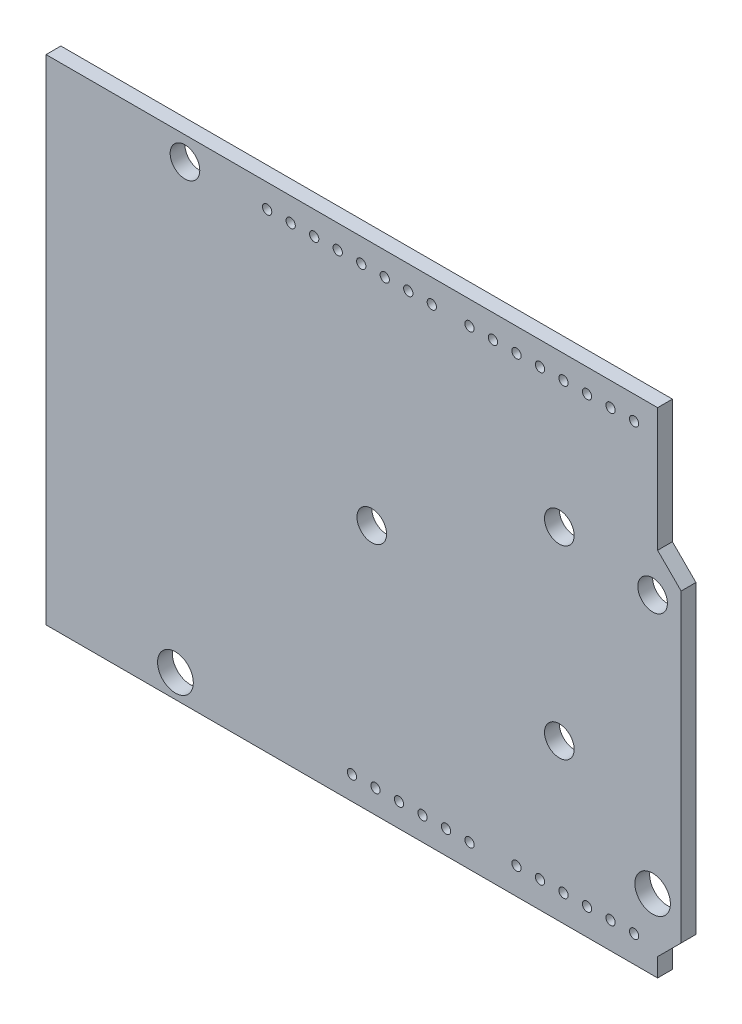
SolidWorks part; units mm, degrees
ref_plane "Front" through (0, 0, 0) normal (0, 0, 1) x (1, 0, 0)
ref_plane "Top" through (0, 0, 0) normal (0, 1, 0) x (1, 0, 0)
ref_plane "Right" through (0, 0, 0) normal (1, 0, 0) x (0, 0, -1)
sketch "草图1" plane through (0, 0, 0) normal (0, 0, 1) x (1, 0, 0)
  line L0 (0, 0) -> (66.04, 0)
  line L1 (66.04, 0) -> (66.04, -13.34)
  line L2 (66.04, -13.34) -> (68.58, -15.88)
  line L3 (68.58, -15.88) -> (68.58, -48.8)
  line L4 (68.58, -48.8) -> (66.04, -51.34)
  line L5 (66.04, -51.34) -> (66.04, -53.34)
  line L6 (66.04, -53.34) -> (0, -53.34)
  line L7 (0, -53.34) -> (0, 0)
  line L8 (45.7314, -50.8) -> (12.3544, -50.8) construction
  line L9 (0, -2.54) -> (66.04, -2.54) construction
  circle A0 centre (45.7314, -50.8) radius 0.5
  circle A1 centre (63.5, -50.46) radius 0.5
  circle A2 centre (43.1914, -50.8) radius 0.5
  circle A3 centre (40.6514, -50.8) radius 0.5
  circle A4 centre (38.1114, -50.8) radius 0.5
  circle A5 centre (35.5714, -50.8) radius 0.5
  circle A6 centre (33.0314, -50.8) radius 0.5
  circle A7 centre (60.96, -50.46) radius 0.5
  circle A8 centre (58.42, -50.46) radius 0.5
  circle A9 centre (55.88, -50.46) radius 0.5
  circle A10 centre (53.34, -50.46) radius 0.5
  circle A11 centre (50.8, -50.46) radius 0.5
  circle A12 centre (15, -2.54) radius 1.6
  circle A13 centre (41.656, -2.54) radius 0.5
  circle A14 centre (63.5, -2.54) radius 0.5
  circle A15 centre (39.116, -2.54) radius 0.5
  circle A16 centre (36.576, -2.54) radius 0.5
  circle A17 centre (34.036, -2.54) radius 0.5
  circle A18 centre (31.496, -2.54) radius 0.5
  circle A19 centre (28.956, -2.54) radius 0.5
  circle A20 centre (26.416, -2.54) radius 0.5
  circle A21 centre (23.876, -2.54) radius 0.5
  circle A22 centre (60.96, -2.54) radius 0.5
  circle A23 centre (58.42, -2.54) radius 0.5
  circle A24 centre (55.88, -2.54) radius 0.5
  circle A25 centre (53.34, -2.54) radius 0.5
  circle A26 centre (50.8, -2.54) radius 0.5
  circle A27 centre (48.26, -2.54) radius 0.5
  circle A28 centre (45.72, -2.54) radius 0.5
  circle A29 centre (13.97, -50.8) radius 1.9317
  circle A30 centre (65.5, -17.78) radius 1.5981
  circle A31 centre (65.5, -45.72) radius 1.9177
  point P77 (0, 0)
  dimension "D9" = 50.8
  dimension "D11" = 1
  dimension "D13" = 3.2
  dimension "D17" = 45.72
  dimension "D3" = 40
  dimension "D4" = 2
  dimension "D5" = 68.58
  dimension "D6" = 135
  dimension "D7" = 5.08
  dimension "D8" = 2.54
  dimension "D14" = 13.97
  dimension "D15" = 15
  dimension "D16" = 2.54
  dimension "D18" = 4.064
  dimension "D20" = 2.54
  dimension "D22" = 7.62
  dimension "D23" = 35.56
  dimension "D24" = 65.5
  dimension "D25" = 53.34
  dimension "D10" = 6
  dimension "D12" = 6
  dimension "D19" = 8
  dimension "D21" = 8
extrude "凸台-拉伸1" add sketch "草图1" along normal blind 1.6
sketch "草图2" plane through (0, 0, 1.6) normal (0, 0, 1) x (1, 0, 0)
  line L0 (55.4285, -16.4661) -> (47.769, -26.4661) construction
  line L1 (47.769, -26.4661) -> (55.4285, -36.4661) construction
  line L2 (35.1726, -26.4661) -> (55.4285, -26.4661) construction
  line L3 (55.4285, -16.4661) -> (55.4285, -36.4661) construction
  line L5 (31.2062, -40.4661) -> (59.2062, -40.4661) construction
  line L6 (31.2062, -40.4661) -> (31.2062, -12.4661) construction
  line L7 (31.2062, -12.4661) -> (59.2062, -12.4661) construction
  line L8 (59.2062, -40.4661) -> (59.2062, -12.4661) construction
  line L9 (31.2062, -40.4661) -> (59.2062, -12.4661) construction
  line L10 (31.2062, -12.4661) -> (59.2062, -40.4661) construction
  circle A0 centre (55.4285, -16.4661) radius 1.6
  circle A1 centre (35.1726, -26.4661) radius 1.6
  circle A2 centre (55.4285, -36.4661) radius 1.6
  circle A4 centre (47.769, -26.4661) radius 12.5964 construction
  point P7 (45.2062, -26.4661)
  point P14 (55.4285, -26.4661)
  point P15 (47.8049, -26.3903)
  point P16 (47.769, -26.4661)
  dimension "D1" = 3.2
  dimension "D2" = 105.099
  dimension "D3" = 28
  dimension "D4" = 45
  dimension "D5" = 20
extrude "切除-拉伸1" cut sketch "草图2" against normal through all
